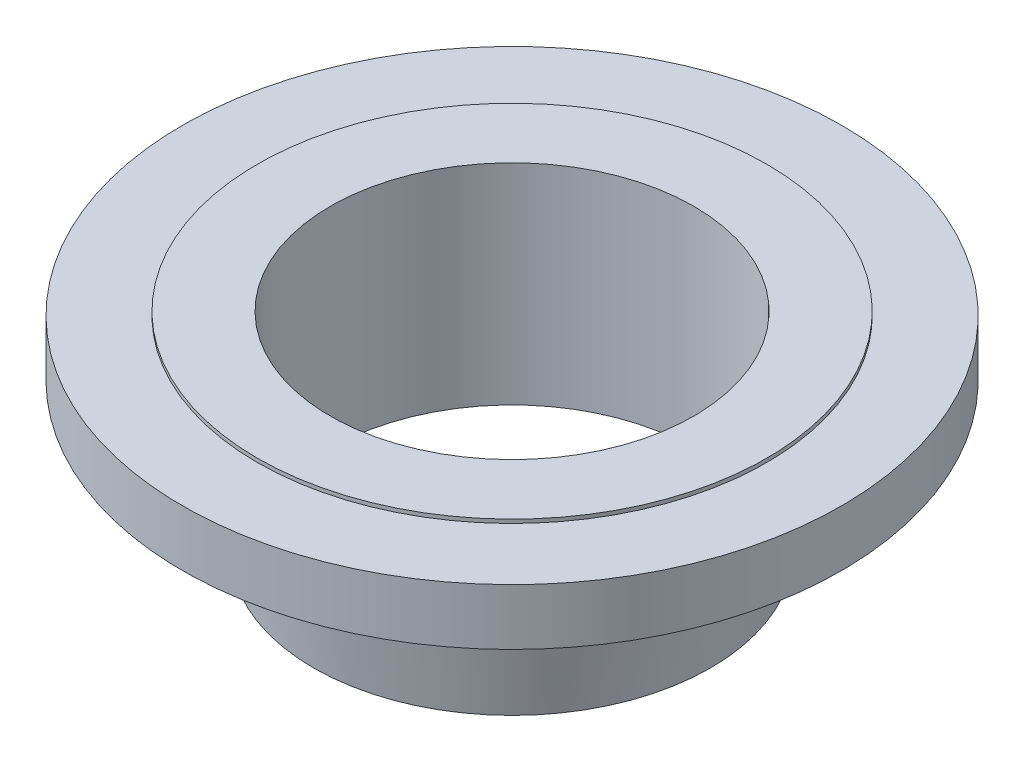
SolidWorks part; units mm, degrees
ref_plane "Front Plane" through (0, 0, 0) normal (0, 0, 1) x (1, 0, 0)
ref_plane "Top Plane" through (0, 0, 0) normal (0, 1, 0) x (1, 0, 0)
ref_plane "Right Plane" through (0, 0, 0) normal (1, 0, 0) x (0, 0, -1)
other "Configuration Table"
sketch "Sketch1" plane through (0, 0, 0) normal (1, 0, 0) x (0, 0, -1)
  line L0 (0, -50) -> (0, 150) construction
  line L1 (77.05, 0) -> (77.05, 88.9)
  line L2 (77.05, 88.9) -> (107.95, 88.9)
  line L3 (107.95, 88.9) -> (107.95, 87.3)
  line L4 (107.95, 87.3) -> (139.7, 87.3)
  line L5 (139.7, 87.3) -> (139.7, 63.5)
  line L6 (139.7, 63.5) -> (92.1, 63.5)
  line L7 (92.1, 63.5) -> (84.15, 0)
  line L8 (84.15, 0) -> (77.05, 0)
revolve "Revolve1" add sketch "Sketch1" angle 360 about L0
